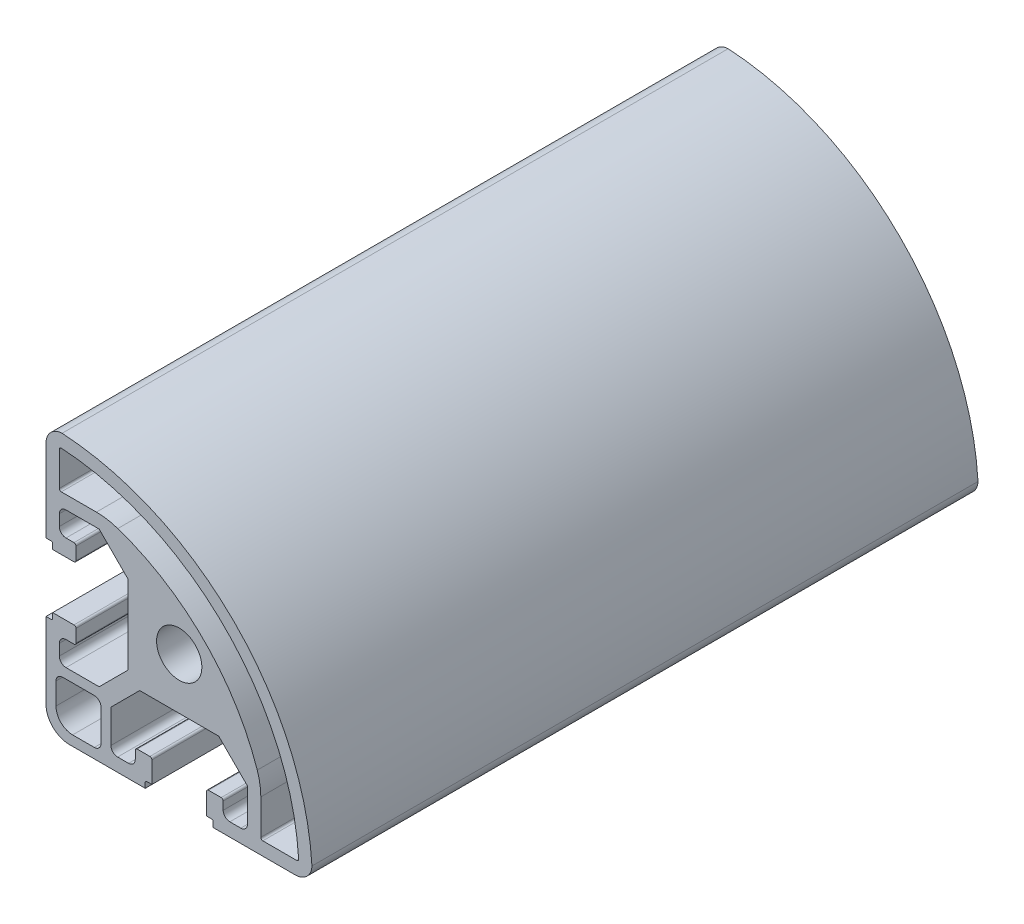
SolidWorks part; units mm, degrees
ref_plane "前视基准面" through (0, 0, 0) normal (0, 0, 1) x (1, 0, 0)
ref_plane "上视基准面" through (0, 0, 0) normal (0, 1, 0) x (1, 0, 0)
ref_plane "右视基准面" through (0, 0, 0) normal (1, 0, 0) x (0, 0, -1)
sketch "草图1" plane through (0, 0, 0) normal (0, 0, 1) x (1, 0, 0)
  line L0 (-15.089, -13.4559) -> (-15.089, -18.2099)
  line L1 (-16.089, -19.2099) -> (-19.343, -19.2099)
  line L2 (-21.843, -16.7099) -> (-21.843, -13.4559)
  line L3 (-20.843, -12.4559) -> (-16.089, -12.4559)
  line L4 (-15.7767, 11.5441) -> (-21.039, 11.5441)
  line L5 (-21.339, 11.8441) -> (-21.339, 16.9238)
  line L6 (14.2908, -18.7059) -> (9.211, -18.7059)
  line L7 (8.911, -18.4059) -> (8.911, -13.1437)
  line L8 (-23.339, 16.7225) -> (-23.339, 4.3941)
  line L9 (-23.339, 4.3941) -> (-22.539, 4.3941)
  line L10 (-22.339, 4.1941) -> (-22.339, 3.3941)
  line L11 (-22.339, 3.3941) -> (-19.139, 3.3941)
  line L12 (-18.839, 3.6941) -> (-18.839, 5.5941)
  line L13 (-19.139, 5.8941) -> (-20.339, 5.8941)
  line L14 (-21.339, 6.8941) -> (-21.339, 8.5441)
  line L15 (-20.339, 9.5441) -> (-15.3567, 9.5441)
  line L16 (-15.3567, 9.5441) -> (-11.039, 5.2263)
  line L17 (-11.039, 5.2263) -> (-11.039, -6.6382)
  line L18 (-11.039, -6.6382) -> (-15.3567, -10.9559)
  line L19 (-15.3567, -10.9559) -> (-20.339, -10.9559)
  line L20 (-21.339, -9.9559) -> (-21.339, -8.3059)
  line L21 (-20.339, -7.3059) -> (-19.139, -7.3059)
  line L22 (-18.839, -7.0059) -> (-18.839, -5.1059)
  line L23 (-19.139, -4.8059) -> (-22.339, -4.8059)
  line L24 (-22.339, -4.8059) -> (-22.339, -5.6059)
  line L25 (-22.539, -5.8059) -> (-23.339, -5.8059)
  line L26 (-23.339, -5.8059) -> (-23.339, -17.2059)
  line L27 (-19.839, -20.7059) -> (-8.439, -20.7059)
  line L28 (-8.439, -20.7059) -> (-8.439, -19.9059)
  line L29 (-8.239, -19.7059) -> (-7.439, -19.7059)
  line L30 (-7.439, -19.7059) -> (-7.439, -16.5059)
  line L31 (-7.739, -16.2059) -> (-9.639, -16.2059)
  line L32 (-9.939, -16.5059) -> (-9.939, -17.7059)
  line L33 (-10.939, -18.7059) -> (-12.589, -18.7059)
  line L34 (-13.589, -17.7059) -> (-13.589, -12.7237)
  line L35 (-13.589, -12.7237) -> (-9.2712, -8.4059)
  line L36 (-9.2712, -8.4059) -> (2.5933, -8.4059)
  line L37 (2.5933, -8.4059) -> (6.911, -12.7237)
  line L38 (6.911, -12.7237) -> (6.911, -17.7059)
  line L39 (5.911, -18.7059) -> (4.261, -18.7059)
  line L40 (3.261, -17.7059) -> (3.261, -16.5059)
  line L41 (2.961, -16.2059) -> (1.061, -16.2059)
  line L42 (0.761, -16.5059) -> (0.761, -19.7059)
  line L43 (0.761, -19.7059) -> (1.561, -19.7059)
  line L44 (1.761, -19.9059) -> (1.761, -20.7059)
  line L45 (1.761, -20.7059) -> (14.0895, -20.7059)
  arc A0 (-16.089, -19.2099) -> (-15.089, -18.2099) centre (-16.089, -18.2099) ccw
  arc A1 (-21.843, -16.7099) -> (-19.343, -19.2099) centre (-19.343, -16.7099) ccw
  arc A2 (-20.843, -12.4559) -> (-21.843, -13.4559) centre (-20.843, -13.4559) ccw
  arc A3 (-15.089, -13.4559) -> (-16.089, -12.4559) centre (-16.089, -13.4559) ccw
  arc A4 (-12.5588, 11.0121) -> (-15.7767, 11.5441) centre (-15.7767, 1.5441) ccw
  arc A5 (-21.339, 11.8441) -> (-21.039, 11.5441) centre (-21.039, 11.8441) ccw
  arc A6 (-21.0207, 17.2233) -> (-21.339, 16.9238) centre (-21.039, 16.9238) ccw
  arc A7 (14.5902, -18.3876) -> (-21.0207, 17.2233) centre (-23.339, -20.7059) ccw
  arc A8 (14.2908, -18.7059) -> (14.5902, -18.3876) centre (14.2908, -18.4059) ccw
  arc A9 (8.911, -18.4059) -> (9.211, -18.7059) centre (9.211, -18.4059) ccw
  arc A10 (8.911, -13.1437) -> (8.3791, -9.9257) centre (-1.089, -13.1437) ccw
  arc A11 (8.3791, -9.9257) -> (-12.5588, 11.0121) centre (-23.339, -20.7059) ccw
  circle A12 centre (-3.339, -0.7059) radius 3.4
  arc A13 (-20.9238, 19.2211) -> (-23.339, 16.7225) centre (-20.839, 16.7225) ccw
  arc A14 (-22.339, 4.1941) -> (-22.539, 4.3941) centre (-22.539, 4.1941) ccw
  arc A15 (-19.139, 3.3941) -> (-18.839, 3.6941) centre (-19.139, 3.6941) ccw
  arc A16 (-18.839, 5.5941) -> (-19.139, 5.8941) centre (-19.139, 5.5941) ccw
  arc A17 (-21.339, 6.8941) -> (-20.339, 5.8941) centre (-20.339, 6.8941) ccw
  arc A18 (-20.339, 9.5441) -> (-21.339, 8.5441) centre (-20.339, 8.5441) ccw
  arc A19 (-21.339, -9.9559) -> (-20.339, -10.9559) centre (-20.339, -9.9559) ccw
  arc A20 (-20.339, -7.3059) -> (-21.339, -8.3059) centre (-20.339, -8.3059) ccw
  arc A21 (-19.139, -7.3059) -> (-18.839, -7.0059) centre (-19.139, -7.0059) ccw
  arc A22 (-18.839, -5.1059) -> (-19.139, -4.8059) centre (-19.139, -5.1059) ccw
  arc A23 (-22.539, -5.8059) -> (-22.339, -5.6059) centre (-22.539, -5.6059) ccw
  arc A24 (-23.339, -17.2059) -> (-19.839, -20.7059) centre (-19.839, -17.2059) ccw
  arc A25 (-8.239, -19.7059) -> (-8.439, -19.9059) centre (-8.239, -19.9059) ccw
  arc A26 (-7.439, -16.5059) -> (-7.739, -16.2059) centre (-7.739, -16.5059) ccw
  arc A27 (-9.639, -16.2059) -> (-9.939, -16.5059) centre (-9.639, -16.5059) ccw
  arc A28 (-10.939, -18.7059) -> (-9.939, -17.7059) centre (-10.939, -17.7059) ccw
  arc A29 (-13.589, -17.7059) -> (-12.589, -18.7059) centre (-12.589, -17.7059) ccw
  arc A30 (5.911, -18.7059) -> (6.911, -17.7059) centre (5.911, -17.7059) ccw
  arc A31 (3.261, -17.7059) -> (4.261, -18.7059) centre (4.261, -17.7059) ccw
  arc A32 (3.261, -16.5059) -> (2.961, -16.2059) centre (2.961, -16.5059) ccw
  arc A33 (1.061, -16.2059) -> (0.761, -16.5059) centre (1.061, -16.5059) ccw
  arc A34 (1.761, -19.9059) -> (1.561, -19.7059) centre (1.561, -19.9059) ccw
  arc A35 (14.0895, -20.7059) -> (16.588, -18.2908) centre (14.0895, -18.2059) ccw
  arc A36 (16.588, -18.2908) -> (-20.9238, 19.2211) centre (-23.339, -20.7059) ccw
extrude "凸台-拉伸1" add sketch "草图1" along normal blind 100
